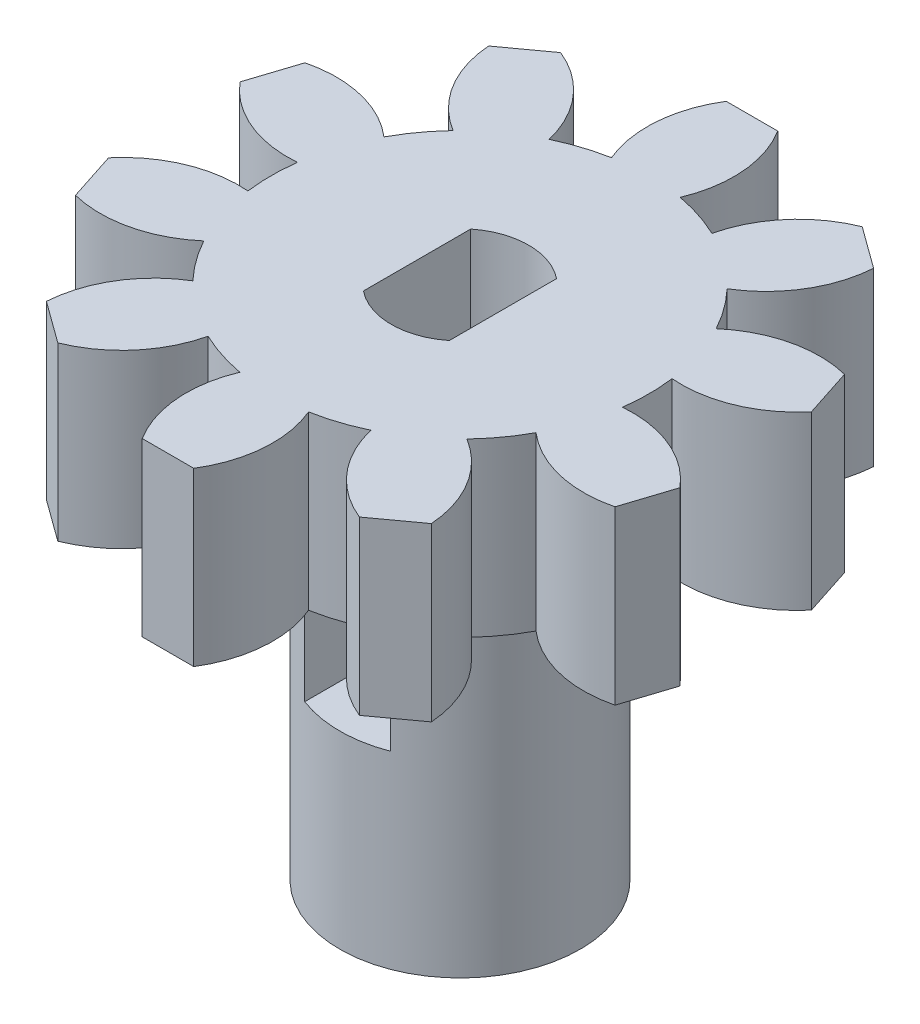
SolidWorks part; units mm, degrees
ref_plane "前视基准面" through (0, 0, 0) normal (0, 0, 1) x (1, 0, 0)
ref_plane "上视基准面" through (0, 0, 0) normal (0, 1, 0) x (1, 0, 0)
ref_plane "右视基准面" through (0, 0, 0) normal (1, 0, 0) x (0, 0, -1)
sketch "草图1" plane through (0, 0, 0) normal (0, 1, 0) x (1, 0, 0)
  circle A0 centre (0, 0) radius 5.5
extrude "凸台-拉伸1" add sketch "草图1" along normal blind 5
sketch "草图2" plane through (0, 5, 0) normal (0, 1, 0) x (-1, 0, 0)
  line L0 (-4.3894, -7.3175) -> (-5.6029, -6.4358)
  line L1 (-7.8522, -3.3399) -> (-8.3157, -1.9134)
  line L2 (-8.3157, 1.9134) -> (-7.8522, 3.3399)
  line L3 (-5.6029, 6.4358) -> (-4.3894, 7.3175)
  line L4 (-0.75, 8.5) -> (0.75, 8.5)
  line L5 (4.3894, 7.3175) -> (5.6029, 6.4358)
  line L6 (0.75, -8.5) -> (-0.75, -8.5)
  line L7 (7.8522, 3.3399) -> (8.3157, 1.9134)
  line L8 (8.3157, -1.9134) -> (7.8522, -3.3399)
  line L9 (5.6029, -6.4358) -> (4.3894, -7.3175)
  arc A0 (-1, -5.4083) -> (1, -5.4083) centre (0, 0) ccw
  arc A1 (-1, -5.4083) -> (-0.75, -8.5) centre (2.1122, -6.7126) ccw
  arc A2 (1, -5.4083) -> (0.75, -8.5) centre (-2.1122, -6.7126) cw
  arc A3 (-3.988, -3.7876) -> (-2.3699, -4.9632) centre (0, 0) ccw
  arc A4 (-3.988, -3.7876) -> (-5.6029, -6.4358) centre (-2.2368, -6.6721) ccw
  arc A5 (-2.3699, -4.9632) -> (-4.3894, -7.3175) centre (-5.6543, -4.1891) cw
  arc A6 (-5.4526, -0.7202) -> (-4.8346, -2.6223) centre (0, 0) ccw
  arc A7 (-5.4526, -0.7202) -> (-8.3157, -1.9134) centre (-5.7314, -4.0831) ccw
  arc A8 (-4.8346, -2.6223) -> (-7.8522, -3.3399) centre (-7.0368, -0.0655) cw
  arc A9 (-4.8346, 2.6223) -> (-5.4526, 0.7202) centre (0, 0) ccw
  arc A10 (-4.8346, 2.6223) -> (-7.8522, 3.3399) centre (-7.0368, 0.0655) ccw
  arc A11 (-5.4526, 0.7202) -> (-8.3157, 1.9134) centre (-5.7314, 4.0831) cw
  arc A12 (-2.3699, 4.9632) -> (-3.988, 3.7876) centre (0, 0) ccw
  arc A13 (-2.3699, 4.9632) -> (-4.3894, 7.3175) centre (-5.6543, 4.1891) ccw
  arc A14 (-3.988, 3.7876) -> (-5.6029, 6.4358) centre (-2.2368, 6.6721) cw
  arc A15 (1, 5.4083) -> (-1, 5.4083) centre (0, 0) ccw
  arc A16 (1, 5.4083) -> (0.75, 8.5) centre (-2.1122, 6.7126) ccw
  arc A17 (-1, 5.4083) -> (-0.75, 8.5) centre (2.1122, 6.7126) cw
  arc A18 (3.988, 3.7876) -> (2.3699, 4.9632) centre (0, 0) ccw
  arc A19 (3.988, 3.7876) -> (5.6029, 6.4358) centre (2.2368, 6.6721) ccw
  arc A20 (2.3699, 4.9632) -> (4.3894, 7.3175) centre (5.6543, 4.1891) cw
  arc A21 (5.4526, 0.7202) -> (4.8346, 2.6223) centre (0, 0) ccw
  arc A22 (5.4526, 0.7202) -> (8.3157, 1.9134) centre (5.7314, 4.0831) ccw
  arc A23 (4.8346, 2.6223) -> (7.8522, 3.3399) centre (7.0368, 0.0655) cw
  arc A24 (4.8346, -2.6223) -> (5.4526, -0.7202) centre (0, 0) ccw
  arc A25 (4.8346, -2.6223) -> (7.8522, -3.3399) centre (7.0368, -0.0655) ccw
  arc A26 (5.4526, -0.7202) -> (8.3157, -1.9134) centre (5.7314, -4.0831) cw
  arc A27 (2.3699, -4.9632) -> (3.988, -3.7876) centre (0, 0) ccw
  arc A28 (2.3699, -4.9632) -> (4.3894, -7.3175) centre (5.6543, -4.1891) ccw
  arc A29 (3.988, -3.7876) -> (5.6029, -6.4358) centre (2.2368, -6.6721) cw
  point P5 (0, -8.5)
  point P13 (-4.9962, -6.8766)
  point P22 (-8.084, -2.6266)
  point P30 (-8.084, 2.6266)
  point P38 (-4.9962, 6.8766)
  point P46 (0, 8.5)
  point P54 (4.9962, 6.8766)
  point P62 (8.084, 2.6266)
  point P70 (8.084, -2.6266)
  point P78 (4.9962, -6.8766)
  dimension "D1" = 10
extrude "凸台-拉伸2" add sketch "草图2" against normal up to surface (5 mm away) up to face at (0, 0, 5.5)
sketch "草图3" plane through (0, 0, 0) normal (0, -1, 0) x (1, 0, 0)
  circle A0 centre (0, 0) radius 3.5
extrude "凸台-拉伸3" add sketch "草图3" along normal blind 10
sketch "草图4" plane through (0, 5, 0) normal (0, 1, 0) x (-1, 0, 0)
  line L2 (1.25, 1.5612) -> (1.25, -1.5612)
  line L4 (-1.25, 1.5612) -> (-1.25, -1.5612)
  arc A0 (-1.25, -1.5612) -> (1.25, -1.5612) centre (0, 0) ccw
  arc A1 (1.25, 1.5612) -> (-1.25, 1.5612) centre (0, 0) ccw
extrude "切除-拉伸1" cut sketch "草图4" against normal through all
sketch "草图5" plane through (0, 0, 0) normal (0, 0, 1) x (1, 0, 0)
  line L0 (-2.3699, 0) -> (-1, 0) construction
  line L1 (-1.25, 0) -> (1.25, 0)
  line L2 (-1.25, 0) -> (-1.25, -4.5)
  line L3 (-1.25, -4.5) -> (1.25, -4.5)
  line L4 (1.25, 0) -> (1.25, -4.5)
  line L5 (-3.5, 0) -> (3.5, 0) construction
extrude "切除-拉伸2" cut sketch "草图5" against normal up to next and the other way up to next
